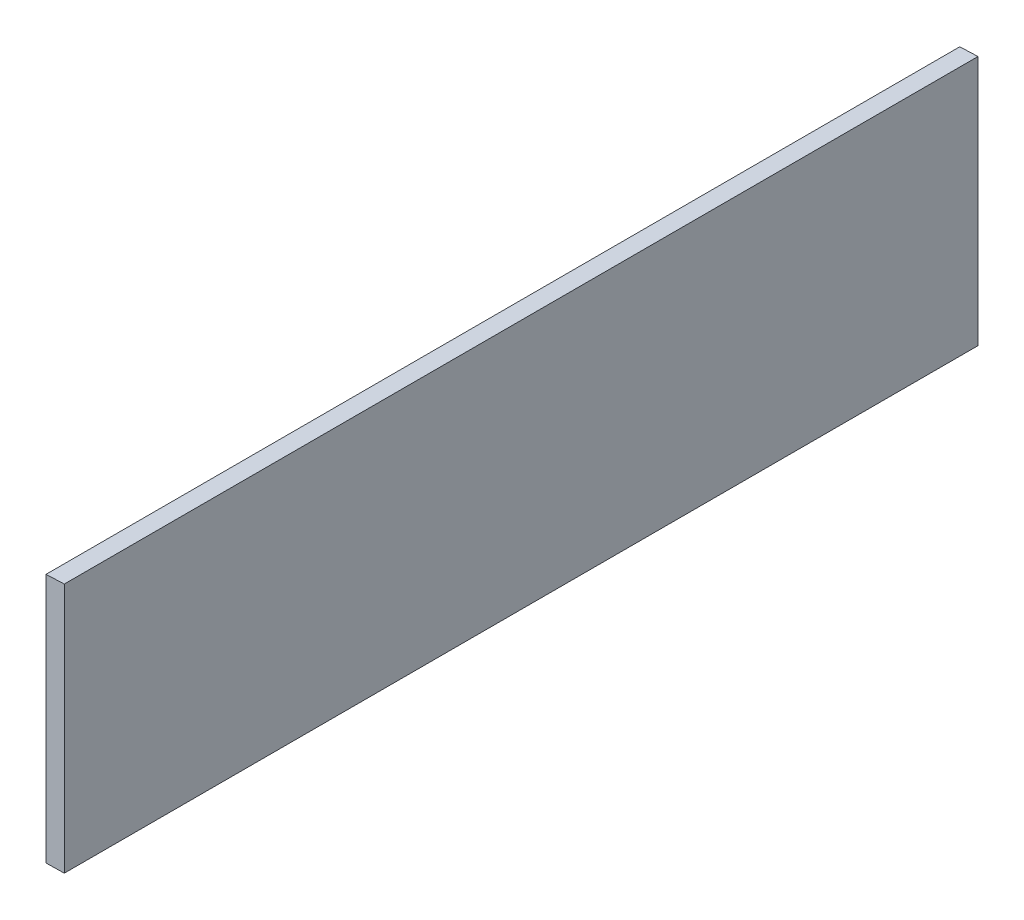
SolidWorks part; units mm, degrees
ref_plane "Front Plane" through (0, 0, 0) normal (0, 0, 1) x (1, 0, 0)
ref_plane "Top Plane" through (0, 0, 0) normal (0, 1, 0) x (1, 0, 0)
ref_plane "Right Plane" through (0, 0, 0) normal (1, 0, 0) x (0, 0, -1)
curve "Curve1"
  spline degree 3 poles (302.6596, 0.1157, 0) (305.3381, -0.0423, 0) (302.669, 0.2207, 0) (300.522, 0.5446, 0) (295.3689, 1.2875, 0) (289.1609, 2.3365, 0) (281.2138, 3.7195, 0) (272.0211, 5.3425, 0) (261.6111, 7.1258, 0) (250.1482, 8.9723, 0) (237.7292, 10.7955, 0) (224.4667, 12.5459, 0) (210.487, 14.2121, 0) (195.9393, 15.7786, 0) (180.9854, 17.2135, 0) (165.7905, 18.4813, 0) (150.5173, 19.555, 0) (135.3259, 20.3976, 0) (120.3737, 20.9834, 0) (105.8119, 21.2902, 0) (91.7835, 21.2891, 0) (78.4214, 20.9725, 0) (65.8465, 20.3288, 0) (54.1674, 19.3419, 0) (43.4744, 18.033, 0) (33.8487, 16.4082, 0) (25.3526, 14.4995, 0) (18.0396, 12.3489, 0) (11.9314, 10.004, 0) (7.0881, 7.5397, 0) (3.4097, 5.063, 0) (1.1505, 2.6895, 0) (-0.3415, 0.4062, 0) (0.6752, -2.0035, 0) (3.5859, -3.0935, 0) (7.5885, -4.3543, 0) (13.2868, -5.2878, 0) (20.4322, -6.0839, 0) (29.0602, -6.6397, 0) (39.0679, -6.9954, 0) (50.3738, -7.1553, 0) (62.8573, -7.1477, 0) (76.3839, -6.9932, 0) (90.8032, -6.6986, 0) (105.9568, -6.2837, 0) (121.6773, -5.7705, 0) (137.79, -5.1759, 0) (154.1149, -4.5178, 0) (170.47, -3.8155, 0) (186.6709, -3.1003, 0) (202.5321, -2.3909, 0) (217.8684, -1.7248, 0) (232.4928, -1.115, 0) (246.2209, -0.6139, 0) (258.8615, -0.2157, 0) (270.2531, 0.0554, 0) (280.189, 0.2196, 0) (288.6505, 0.2748, 0) (295.1556, 0.2617, 0) (300.4646, 0.1437, 0) (302.6596, 0.1157, 0) (305.3381, -0.0423, 0) (302.669, 0.2207, 0) knots -0.014411 -0.006469 -0.001624 0 0.001633 0.006456 0.014273 0.024844 0.037882 0.053108 0.070262 0.089112 0.109474 0.131183 0.154044 0.177808 0.202202 0.22696 0.251816 0.276516 0.300807 0.324444 0.347208 0.368894 0.389314 0.408315 0.425773 0.441588 0.45568 0.468012 0.478567 0.487363 0.494419 0.499795 0.503598 0.50652 0.511061 0.517924 0.527205 0.538874 0.552882 0.569133 0.587486 0.607759 0.629726 0.653145 0.677762 0.703306 0.729491 0.756024 0.782609 0.80895 0.834737 0.859675 0.88346 0.905785 0.926349 0.944858 0.961055 0.974701 0.985589 0.993531 0.998376 1 1.001633 1.006456 1.014273 periodic
sketch "Sketch1" plane through (0, 0, 0) normal (0, 0, 1) x (1, 0, 0)
  line L0 (76.2, 20.8248) -> (76.2, -6.975)
  line L1 (78.232, 20.9058) -> (78.232, -6.9415)
  spline S0 degree 3 poles (302.6596, 0.1157) (305.3381, -0.0423) (302.669, 0.2207) (300.522, 0.5446) (295.3689, 1.2875) (289.1609, 2.3365) (281.2138, 3.7195) (272.0211, 5.3425) (261.6111, 7.1258) (250.1482, 8.9723) (237.7292, 10.7955) (224.4667, 12.5459) (210.487, 14.2121) (195.9393, 15.7786) (180.9854, 17.2135) (165.7905, 18.4813) (150.5173, 19.555) (135.3259, 20.3976) (120.3737, 20.9834) (105.8119, 21.2902) (91.7835, 21.2891) (78.4214, 20.9725) (65.8465, 20.3288) (54.1674, 19.3419) (43.4744, 18.033) (33.8487, 16.4082) (25.3526, 14.4995) (18.0396, 12.3489) (11.9314, 10.004) (7.0881, 7.5397) (3.4097, 5.063) (1.1505, 2.6895) (-0.3415, 0.4062) (0.6752, -2.0035) (3.5859, -3.0935) (7.5885, -4.3543) (13.2868, -5.2878) (20.4322, -6.0839) (29.0602, -6.6397) (39.0679, -6.9954) (50.3738, -7.1553) (62.8573, -7.1477) (76.3839, -6.9932) (90.8032, -6.6986) (105.9568, -6.2837) (121.6773, -5.7705) (137.79, -5.1759) (154.1149, -4.5178) (170.47, -3.8155) (186.6709, -3.1003) (202.5321, -2.3909) (217.8684, -1.7248) (232.4928, -1.115) (246.2209, -0.6139) (258.8615, -0.2157) (270.2531, 0.0554) (280.189, 0.2196) (288.6505, 0.2748) (295.1556, 0.2617) (300.4646, 0.1437) (302.6596, 0.1157) (305.3381, -0.0423) (302.669, 0.2207) knots -0.014411 -0.006469 -0.001624 0 0.001633 0.006456 0.014273 0.024844 0.037882 0.053108 0.070262 0.089112 0.109474 0.131183 0.154044 0.177808 0.202202 0.22696 0.251816 0.276516 0.300807 0.324444 0.347208 0.368894 0.389314 0.408315 0.425773 0.441588 0.45568 0.468012 0.478567 0.487363 0.494419 0.499795 0.503598 0.50652 0.511061 0.517924 0.527205 0.538874 0.552882 0.569133 0.587486 0.607759 0.629726 0.653145 0.677762 0.703306 0.729491 0.756024 0.782609 0.80895 0.834737 0.859675 0.88346 0.905785 0.926349 0.944858 0.961055 0.974701 0.985589 0.993531 0.998376 1 1.001633 1.006456 1.014273 only from (304.8, 0) to (304.8, 0) construction
  spline S1 degree 3 poles (302.6596, 0.1157) (305.3381, -0.0423) (302.669, 0.2207) (300.522, 0.5446) (295.3689, 1.2875) (289.1609, 2.3365) (281.2138, 3.7195) (272.0211, 5.3425) (261.6111, 7.1258) (250.1482, 8.9723) (237.7292, 10.7955) (224.4667, 12.5459) (210.487, 14.2121) (195.9393, 15.7786) (180.9854, 17.2135) (165.7905, 18.4813) (150.5173, 19.555) (135.3259, 20.3976) (120.3737, 20.9834) (105.8119, 21.2902) (91.7835, 21.2891) (78.4214, 20.9725) (65.8465, 20.3288) (54.1674, 19.3419) (43.4744, 18.033) (33.8487, 16.4082) (25.3526, 14.4995) (18.0396, 12.3489) (11.9314, 10.004) (7.0881, 7.5397) (3.4097, 5.063) (1.1505, 2.6895) (-0.3415, 0.4062) (0.6752, -2.0035) (3.5859, -3.0935) (7.5885, -4.3543) (13.2868, -5.2878) (20.4322, -6.0839) (29.0602, -6.6397) (39.0679, -6.9954) (50.3738, -7.1553) (62.8573, -7.1477) (76.3839, -6.9932) (90.8032, -6.6986) (105.9568, -6.2837) (121.6773, -5.7705) (137.79, -5.1759) (154.1149, -4.5178) (170.47, -3.8155) (186.6709, -3.1003) (202.5321, -2.3909) (217.8684, -1.7248) (232.4928, -1.115) (246.2209, -0.6139) (258.8615, -0.2157) (270.2531, 0.0554) (280.189, 0.2196) (288.6505, 0.2748) (295.1556, 0.2617) (300.4646, 0.1437) (302.6596, 0.1157) (305.3381, -0.0423) (302.669, 0.2207) knots -0.014411 -0.006469 -0.001624 0 0.001633 0.006456 0.014273 0.024844 0.037882 0.053108 0.070262 0.089112 0.109474 0.131183 0.154044 0.177808 0.202202 0.22696 0.251816 0.276516 0.300807 0.324444 0.347208 0.368894 0.389314 0.408315 0.425773 0.441588 0.45568 0.468012 0.478567 0.487363 0.494419 0.499795 0.503598 0.50652 0.511061 0.517924 0.527205 0.538874 0.552882 0.569133 0.587486 0.607759 0.629726 0.653145 0.677762 0.703306 0.729491 0.756024 0.782609 0.80895 0.834737 0.859675 0.88346 0.905785 0.926349 0.944858 0.961055 0.974701 0.985589 0.993531 0.998376 1 1.001633 1.006456 1.014273 only from (304.8, 0) to (304.8, 0)
  point P1 (50.8, -7.1286)
  dimension "D1" = 76.2
  dimension "D2" = 2.032
extrude "Boss-Extrude1" add sketch "Sketch1" along normal blind 101.6 contours L1 S1 L0
